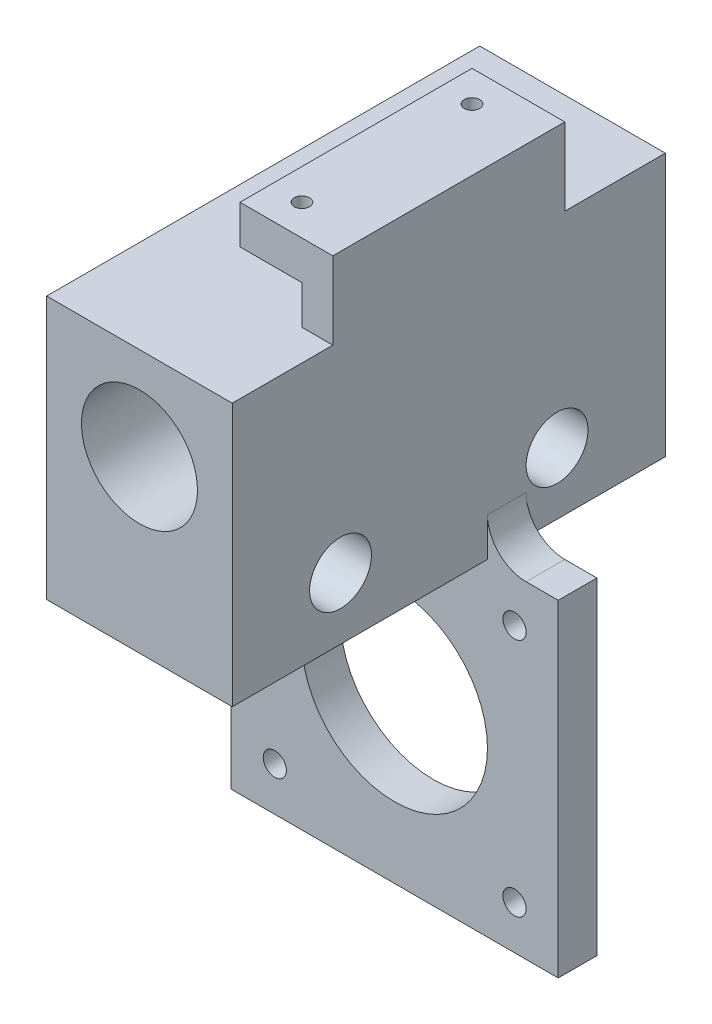
SolidWorks part; units mm, degrees
ref_plane "Front Plane" through (0, 0, 0) normal (0, 0, 1) x (1, 0, 0)
ref_plane "Top Plane" through (0, 0, 0) normal (0, 1, 0) x (1, 0, 0)
ref_plane "Right Plane" through (0, 0, 0) normal (1, 0, 0) x (0, 0, -1)
sketch "Sketch1" plane through (0, 0, 0) normal (0, 0, 1) x (1, 0, 0)
  line L1 (-12, 12) -> (12, 12)
  line L2 (-12, 12) -> (-12, -22)
  line L3 (-12, -22) -> (12, -22)
  line L4 (12, 12) -> (12, -22)
  circle A0 centre (0, 0) radius 7.5
  dimension "D1" = 12
  dimension "D5" = 15
  dimension "D2" = 24
  dimension "D3" = 12
  dimension "D4" = 34
extrude "Boss-Extrude1" add sketch "Sketch1" along normal mid plane 56
sketch "Sketch5" plane through (0, 12, 0) normal (0, 1, 0) x (1, 0, 0)
  line L0 (12, -28) -> (12, 28) construction
  line L1 (0, 15) -> (12, 15)
  line L2 (0, 15) -> (0, -15)
  line L3 (0, -15) -> (12, -15)
  line L4 (12, 15) -> (12, -15)
  point P6 (12, 0)
  dimension "D1" = 30
  dimension "D2" = 12
extrude "Boss-Extrude3" add sketch "Sketch5" along normal blind 10
sketch "Sketch6" plane through (0, 0, 15) normal (0, 0, 1) x (1, 0, 0)
  line L0 (0, 22) -> (0, 12) construction
  line L1 (0, 17) -> (8, 17)
  line L2 (0, 17) -> (0, 12)
  line L3 (0, 12) -> (8, 12)
  line L4 (8, 17) -> (8, 12)
  line L5 (0, 12) -> (12, 12) construction
  dimension "D1" = 8
  dimension "D2" = 5
extrude "Cut-Extrude3" cut sketch "Sketch6" against normal through all
sketch "Sketch7" plane through (0, 22, 0) normal (0, 1, 0) x (1, 0, 0)
  line L0 (0, -15) -> (12, -15) construction
  line L1 (0, 15) -> (0, -15) construction
  line L3 (12, 15) -> (0, 15) construction
  circle A0 centre (4, 11) radius 1
  circle A1 centre (4, -11) radius 1
  dimension "D1" = 2
  dimension "D2" = 4
  dimension "D3" = 4
  dimension "D4" = 4
  dimension "D5" = 4
extrude "Cut-Extrude4" cut sketch "Sketch7" against normal up to next
sketch "Sketch8" plane through (12, 0, 0) normal (1, 0, 0) x (0, 0, -1)
  line L2 (-28, -22) -> (28, -22) construction
  circle A0 centre (-14, -14) radius 4
  circle A1 centre (14, -14) radius 4
  dimension "D1" = 8
  dimension "D2" = 28
  dimension "D4" = 8
  dimension "D5" = 14
extrude "Cut-Extrude5" cut sketch "Sketch8" against normal blind 20
sketch "Sketch9" plane through (0, -22, 0) normal (0, -1, 0) x (1, 0, 0)
  line L1 (-21.15, -5) -> (21.15, -5)
  line L2 (-21.15, -5) -> (-21.15, -10)
  line L3 (-21.15, -10) -> (21.15, -10)
  line L4 (21.15, -5) -> (21.15, -10)
  dimension "D1" = 10
  dimension "D2" = 5
  dimension "D3" = 42.3
  dimension "D4" = 21.15
extrude "Boss-Extrude4" add sketch "Sketch9" along normal blind 42.3
sketch "Sketch10" plane through (0, 0, -10) normal (0, 0, -1) x (-1, 0, 0)
  line L0 (21.15, -22) -> (12, -22) construction
  line L1 (21.15, -64.3) -> (21.15, -22) construction
  circle A0 centre (0, -43.15) radius 12
  circle A1 centre (-15.5, -27.65) radius 1.5
  circle A2 centre (15.5, -27.65) radius 1.5
  circle A3 centre (15.5, -58.65) radius 1.5
  circle A4 centre (-15.5, -58.65) radius 1.5
  dimension "D1" = 24
  dimension "D4" = 3
  dimension "D2" = 21.15
  dimension "D3" = 21.15
  dimension "D5" = 15.5
  dimension "D6" = 31
  dimension "D7" = 31
  dimension "D8" = 15.5
  dimension "D9" = 31
extrude "Cut-Extrude6" cut sketch "Sketch10" against normal blind 48
fillet "Fillet1" radius 5 1 edges at (-12, -22, -7.5)
fillet "Fillet2" radius 5 1 edges at (12, -22, -7.5)
